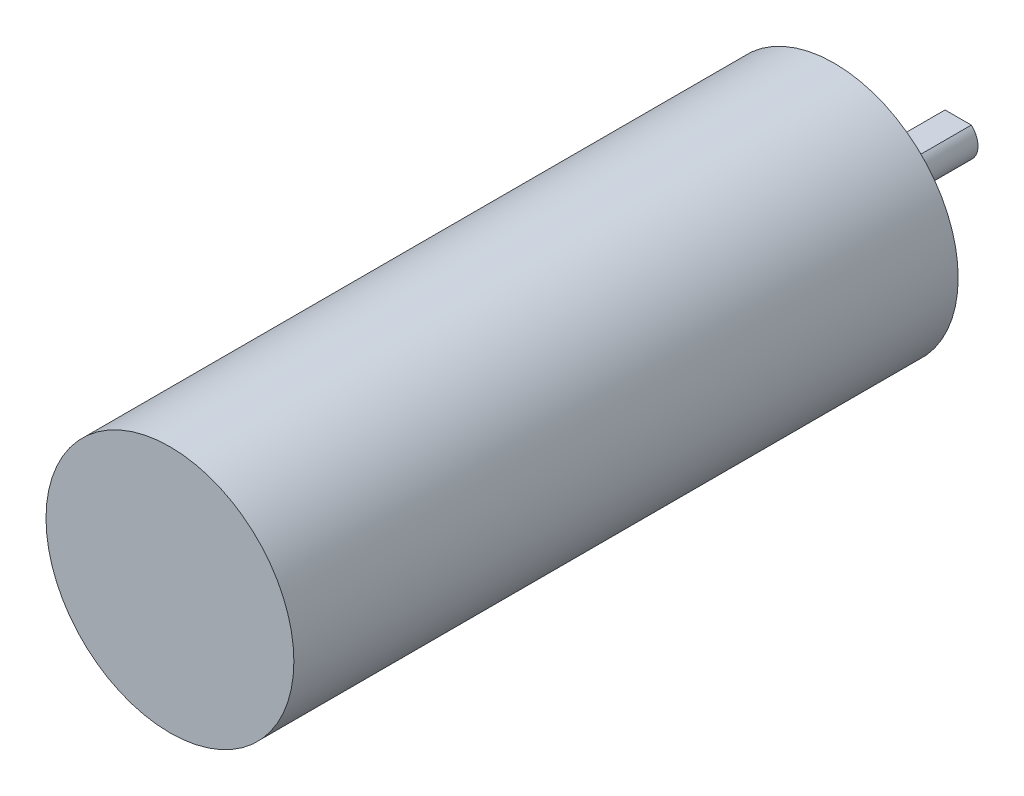
SolidWorks part; units mm, degrees
ref_plane "Front Plane" through (0, 0, 0) normal (0, 0, 1) x (1, 0, 0)
ref_plane "Top Plane" through (0, 0, 0) normal (0, 1, 0) x (1, 0, 0)
ref_plane "Right Plane" through (0, 0, 0) normal (1, 0, 0) x (0, 0, -1)
sketch "Sketch1" plane through (0, 0, 0) normal (0, 0, 1) x (1, 0, 0)
  circle A0 centre (0, 0) radius 12.5
  dimension "D1" = 25
extrude "Boss-Extrude1" add sketch "Sketch1" along normal blind 67
sketch "Sketch2" plane through (0, 0, 0) normal (0, 0, -1) x (-1, 0, 0)
  circle A0 centre (0, 0) radius 3.5
  dimension "D1" = 7
extrude "Boss-Extrude2" add sketch "Sketch2" along normal blind 2.5
sketch "Sketch3" plane through (0, 0, -2.5) normal (0, 0, -1) x (-1, 0, 0)
  line L0 (-1.3229, 1.5) -> (1.3229, 1.5)
  line L1 (0, -2) -> (4.0207, -2) construction
  arc A0 (-1.3229, 1.5) -> (1.3229, 1.5) centre (0, 0) ccw
  point P6 (0, 1.5)
  dimension "D1" = 4
  dimension "D2" = 3.5
extrude "Boss-Extrude3" add sketch "Sketch3" along normal blind 10
sketch "Sketch4" plane through (0, 0, 0) normal (0, 0, -1) x (-1, 0, 0)
  line L0 (0, 0) -> (0, 8.5) construction
  line L1 (0, 0) -> (9.8989, 0) construction
  circle A0 centre (0, 8.5) radius 1.5
  dimension "D1" = 3
  dimension "D2" = 8.5
extrude "Cut-Extrude1" cut sketch "Sketch4" against normal blind 12.7
mirror "Mirror1" about plane through (0, 0, 0) normal (0, 1, 0) of "Cut-Extrude1"
